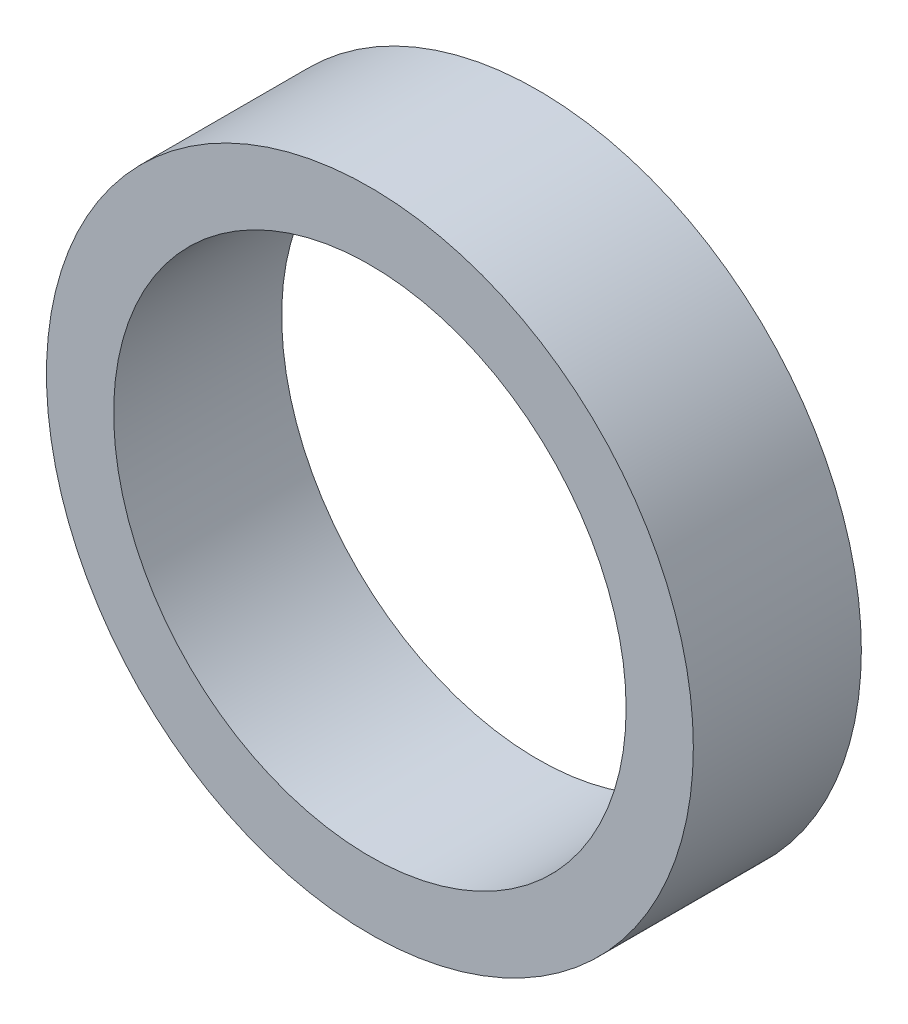
SolidWorks part; units mm, degrees
ref_plane "前视基准面" through (0, 0, 0) normal (0, 0, 1) x (1, 0, 0)
ref_plane "上视基准面" through (0, 0, 0) normal (0, 1, 0) x (1, 0, 0)
ref_plane "右视基准面" through (0, 0, 0) normal (1, 0, 0) x (0, 0, -1)
sketch "草图1" plane through (0, 0, 0) normal (0, 0, 1) x (1, 0, 0)
  circle A0 centre (0, 0) radius 1.925
  circle A1 centre (0, 0) radius 1.525
  dimension "D1" = 3.05
  dimension "D2" = 0.4
extrude "凸台-拉伸1" add sketch "草图1" along normal blind 1
